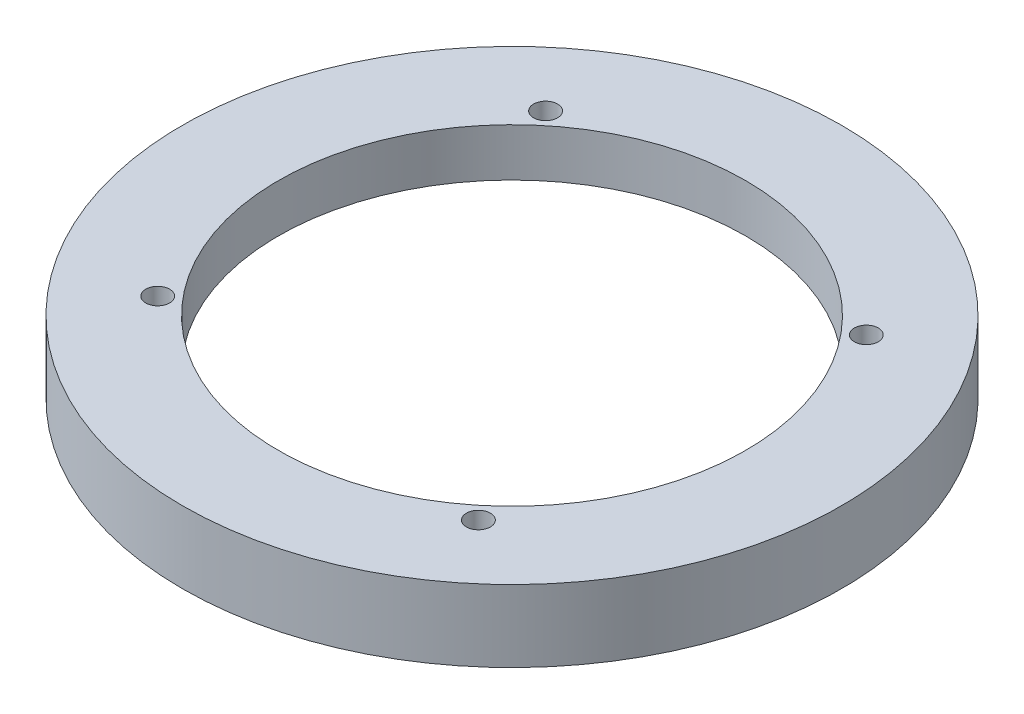
SolidWorks part; units mm, degrees
ref_plane "前视基准面" through (0, 0, 0) normal (0, 0, 1) x (1, 0, 0)
ref_plane "上视基准面" through (0, 0, 0) normal (0, 1, 0) x (1, 0, 0)
ref_plane "右视基准面" through (0, 0, 0) normal (1, 0, 0) x (0, 0, -1)
sketch "草图2" plane through (0, 0, 0) normal (0, 1, 0) x (1, 0, 0)
  circle A0 centre (0, 0) radius 117.5
  circle A1 centre (0, 0) radius 137.5
  dimension "D1" = 235
  dimension "D2" = 20
extrude "凸台-拉伸1" add sketch "草图2" along normal blind 10
sketch "草图3" plane through (0, 10, 0) normal (0, 1, 0) x (1, 0, 0)
  circle A0 centre (0, 0) radius 137.5
extrude "凸台-拉伸2" add sketch "草图3" along normal blind 20
sketch "草图4" plane through (0, 10, 0) normal (0, -1, 0) x (1, 0, 0)
  circle A0 centre (0, 0) radius 97.5
  dimension "D1" = 195
extrude "切除-拉伸1" cut sketch "草图4" against normal through all
sketch "草图6" plane through (0, 30, 0) normal (0, 1, 0) x (1, 0, 0)
  circle A0 centre (80.9224, 66.9071) radius 5 construction
  circle A1 centre (66.9071, -80.9224) radius 5 construction
  circle A2 centre (-80.9224, -66.9071) radius 5 construction
  circle A3 centre (-66.9071, 80.9224) radius 5 construction
  circle A4 centre (80.9224, 66.9071) radius 5
  circle A5 centre (66.9071, -80.9224) radius 5
  circle A6 centre (-80.9224, -66.9071) radius 5
  circle A7 centre (-66.9071, 80.9224) radius 5
extrude "切除-拉伸2" cut sketch "草图6" against normal through all both and the other way through all
